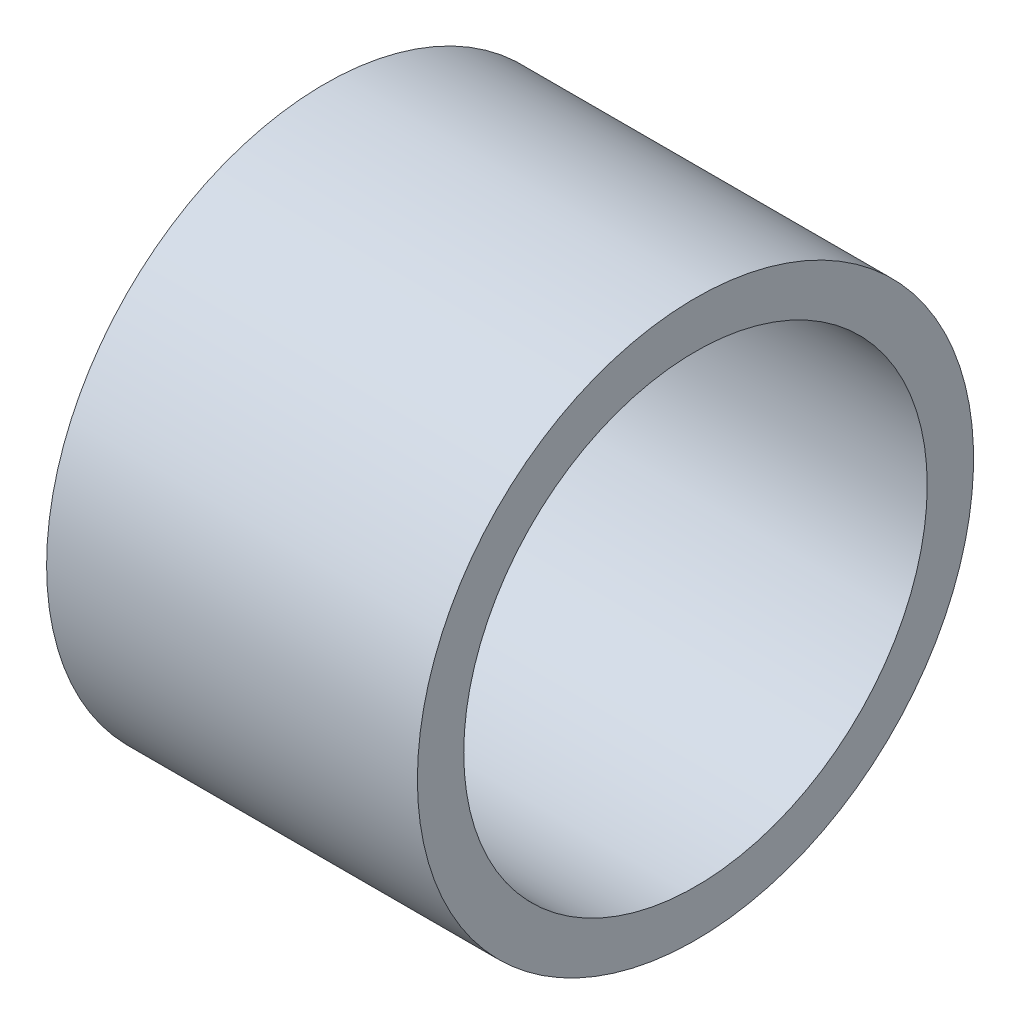
SolidWorks part; units mm, degrees
ref_plane "Płaszczyzna przednia" through (0, 0, 0) normal (0, 0, 1) x (1, 0, 0)
ref_plane "Płaszczyzna górna" through (0, 0, 0) normal (0, 1, 0) x (1, 0, 0)
ref_plane "Płaszczyzna prawa" through (0, 0, 0) normal (1, 0, 0) x (0, 0, -1)
sketch "Szkic1" plane through (0, 0, 0) normal (0, 0, 1) x (1, 0, 0)
  line L1 (-13, 12) -> (-29, 12)
  line L2 (-13, 12) -> (-13, 10)
  line L3 (-13, 10) -> (-29, 10)
  line L4 (-29, 12) -> (-29, 10)
  line L6 (-26.6696, 0) -> (-3.8852, 0) construction
  dimension "D1" = 16
  dimension "D2" = 2
  dimension "D3" = 20
revolve "Obrót1" add sketch "Szkic1" angle 360 about L6
